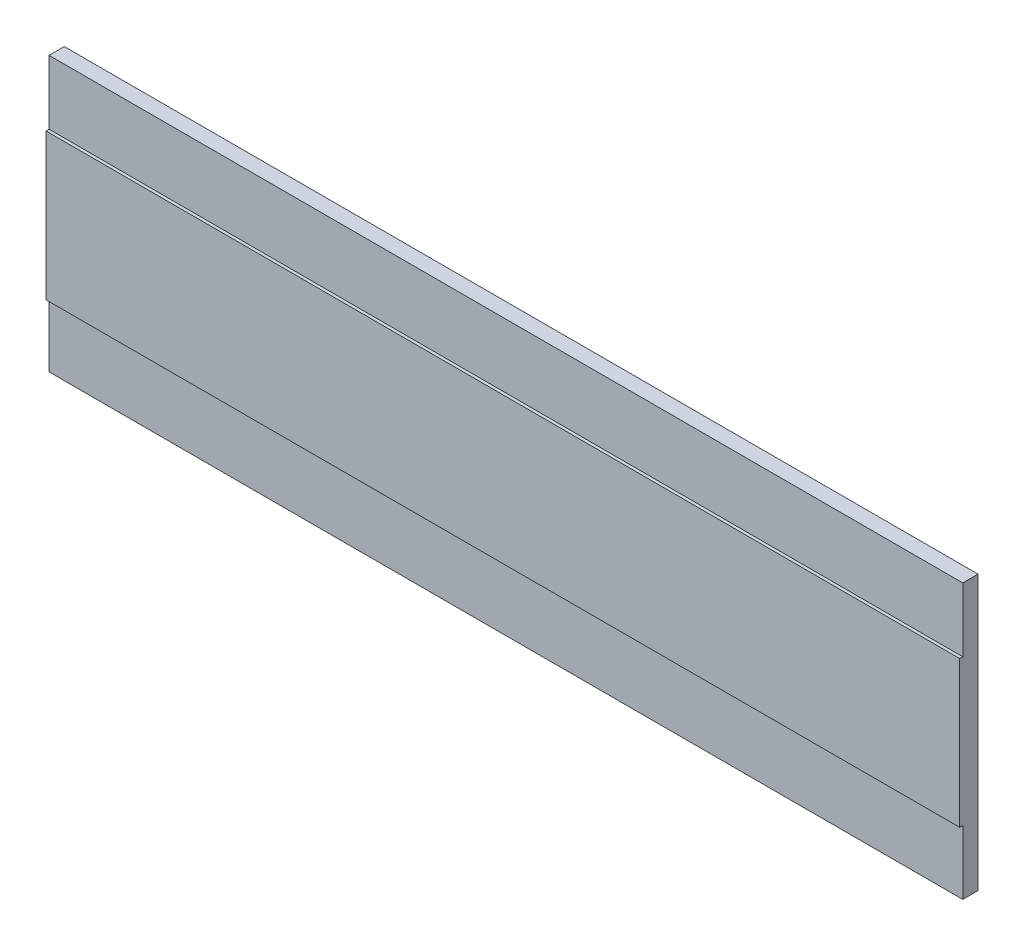
SolidWorks part; units mm, degrees
material "1.0037 (S235JR)"
ref_plane "Płaszczyzna przednia" through (0, 0, 0) normal (0, 0, 1) x (1, 0, 0)
ref_plane "Płaszczyzna górna" through (0, 0, 0) normal (0, 1, 0) x (1, 0, 0)
ref_plane "Płaszczyzna prawa" through (0, 0, 0) normal (1, 0, 0) x (0, 0, -1)
sketch "Szkic1" plane through (0, 0, 0) normal (0, 0, 1) x (1, 0, 0)
  line L1 (0, 450) -> (600, 450)
  line L2 (0, 450) -> (0, 270)
  line L3 (0, 270) -> (600, 270)
  line L4 (600, 450) -> (600, 270)
  line L6 (0, 430) -> (0, -20) construction
  line L7 (600, 430) -> (600, -20) construction
  line L8 (520, 430) -> (80, 430) construction
  dimension "D1" = 180
  dimension "D2" = 20
extrude "Dodanie-wyciągnięcie1" add sketch "Szkic1" along normal blind 10
sketch "Szkic2" plane through (0, 0, 10) normal (0, 0, 1) x (1, 0, 0)
  line L1 (0, 450) -> (0, 270) construction
  line L3 (0, 408) -> (600, 408)
  line L4 (0, 408) -> (0, 312)
  line L5 (600, 270) -> (600, 450) construction
  line L6 (0, 360) -> (600, 360) construction
  line L7 (0, 312) -> (600, 312)
  line L8 (600, 408) -> (600, 312)
  dimension "D1" = 96
extrude "Dodanie-wyciągnięcie2" add sketch "Szkic2" along normal blind 2
sketch "Szkic3" plane through (0, 0, 12) normal (0, 0, 1) x (1, 0, 0)
  line L0 (600, 312) -> (600, 408) construction
  line L1 (0, 360) -> (73, 360) construction
  line L2 (0, 408) -> (0, 312) construction
  line L3 (600, 331) -> (558, 331)
  line L4 (0, 390) -> (73, 390)
  line L5 (0, 390) -> (0, 330)
  line L6 (0, 330) -> (73, 330)
  line L7 (73, 390) -> (73, 330)
  line L8 (600, 331) -> (600, 389)
  line L9 (600, 389) -> (558, 389)
  line L10 (558, 331) -> (558, 389)
  line L11 (558, 360) -> (600, 360) construction
  dimension "D1" = 60
  dimension "D2" = 73
  dimension "D3" = 58
  dimension "D4" = 42
